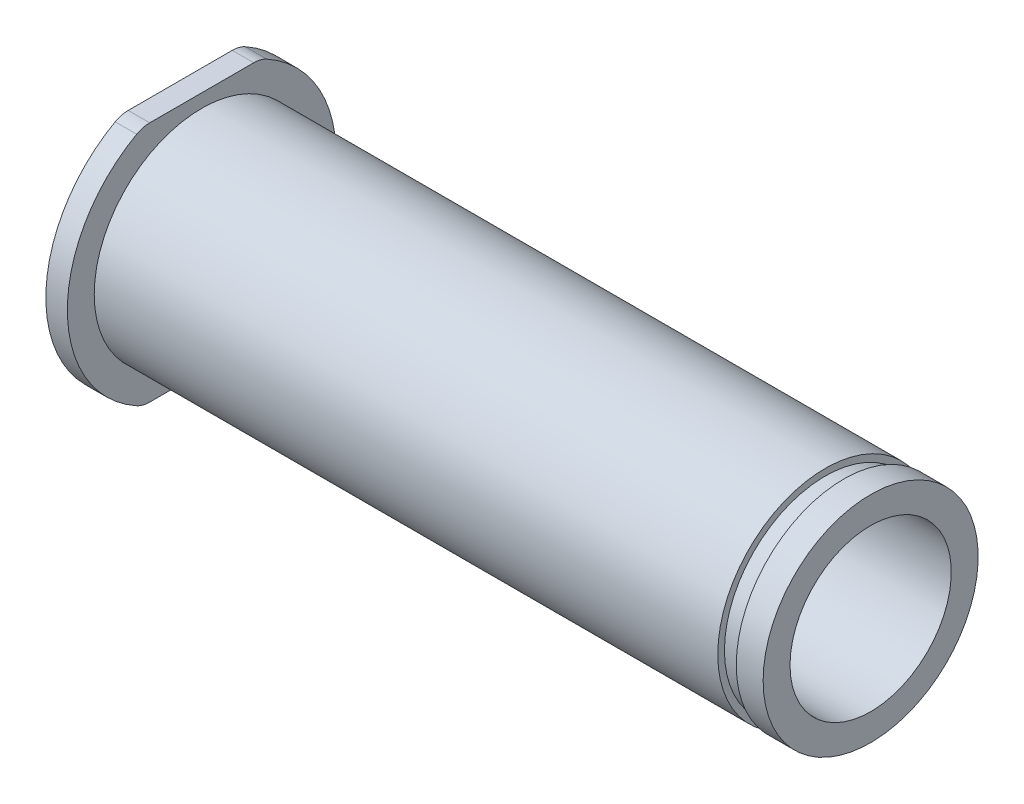
SolidWorks part; units mm, degrees
material "6061 Alloy"
ref_plane "Front Plane" through (0, 0, 0) normal (0, 0, 1) x (1, 0, 0)
ref_plane "Top Plane" through (0, 0, 0) normal (0, 1, 0) x (1, 0, 0)
ref_plane "Right Plane" through (0, 0, 0) normal (1, 0, 0) x (0, 0, -1)
sketch "Sketch1" plane through (0, 0, 0) normal (0, 0, 1) x (1, 0, 0)
  line L0 (0, 0) -> (81.5594, 0) construction
  line L1 (0, 9.525) -> (81.5594, 9.525)
  line L2 (81.5594, 9.525) -> (81.5594, 12.7)
  line L3 (81.5594, 12.7) -> (78.3844, 12.7)
  line L4 (78.3844, 12.7) -> (78.3844, 11.9126)
  line L5 (78.3844, 11.9126) -> (76.2, 11.9126)
  line L6 (76.2, 11.9126) -> (76.2, 12.7)
  line L7 (76.2, 12.7) -> (2.54, 12.7)
  line L8 (2.54, 12.7) -> (2.54, 15.875)
  line L9 (2.54, 15.875) -> (0, 15.875)
  line L10 (0, 15.875) -> (0, 9.525)
  dimension "D1" = 76.2
  dimension "D2" = 2.54
  dimension "D3" = 31.75
  dimension "D4" = 25.4
  dimension "D5" = 2.1844
  dimension "D6" = 23.8252
  dimension "D7" = 3.175
  dimension "D8" = 19.05
revolve "Revolve1" add sketch "Sketch1" angle 360 about L0
sketch "Sketch2" plane through (0, 0, 0) normal (-1, 0, 0) x (0, 0, 1)
  line L0 (-6.9198, 14.2875) -> (6.9198, 14.2875)
  line L1 (6.9198, 14.2875) -> (6.9198, 15.875)
  line L2 (6.9198, 15.875) -> (-6.9198, 15.875)
  line L3 (-6.9198, 15.875) -> (-6.9198, 14.2875)
  line L4 (-6.9198, -14.2875) -> (6.9198, -14.2875)
  line L5 (6.9198, -14.2875) -> (6.9198, -15.875)
  line L6 (6.9198, -15.875) -> (-6.9198, -15.875)
  line L7 (-6.9198, -15.875) -> (-6.9198, -14.2875)
  line L8 (0, 14.2875) -> (0, -14.2875) construction
  circle A0 centre (0, 0) radius 15.875 construction
  dimension "D1" = 28.575
extrude "Cut-Extrude1" cut sketch "Sketch2" against normal up to next
fillet "Fillet1" radius 3.175 4 edges at (1.27, -14.2875, 6.9198) (1.27, -14.2875, -6.9198) (1.27, 14.2875, -6.9198) (1.27, 14.2875, 6.9198)
